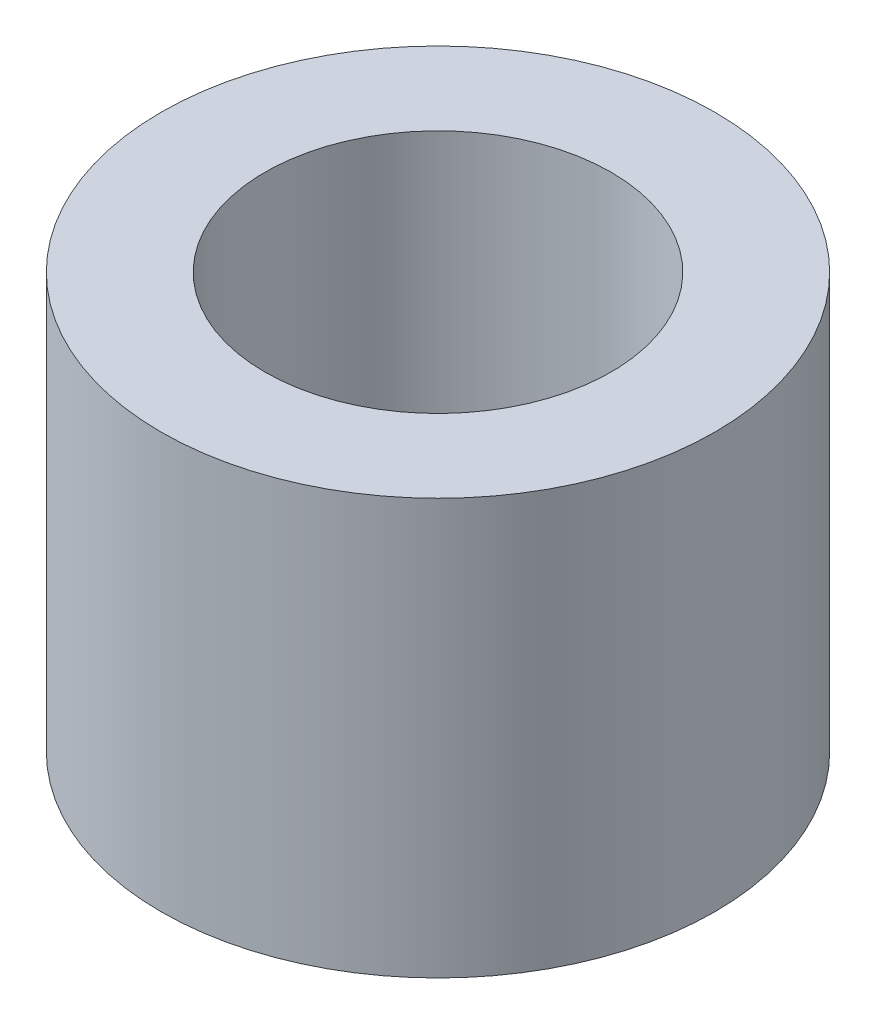
SolidWorks part; units mm, degrees
ref_plane "Front Plane" through (0, 0, 0) normal (0, 0, 1) x (1, 0, 0)
ref_plane "Top Plane" through (0, 0, 0) normal (0, 1, 0) x (1, 0, 0)
ref_plane "Right Plane" through (0, 0, 0) normal (1, 0, 0) x (0, 0, -1)
sketch "Sketch1" plane through (0, 0, 0) normal (0, 1, 0) x (1, 0, 0)
  circle A0 centre (0, 0) radius 4
  circle A1 centre (0, 0) radius 2.5
  dimension "D1" = 8
  dimension "D2" = 5
extrude "Boss-Extrude1" add sketch "Sketch1" along normal blind 6
